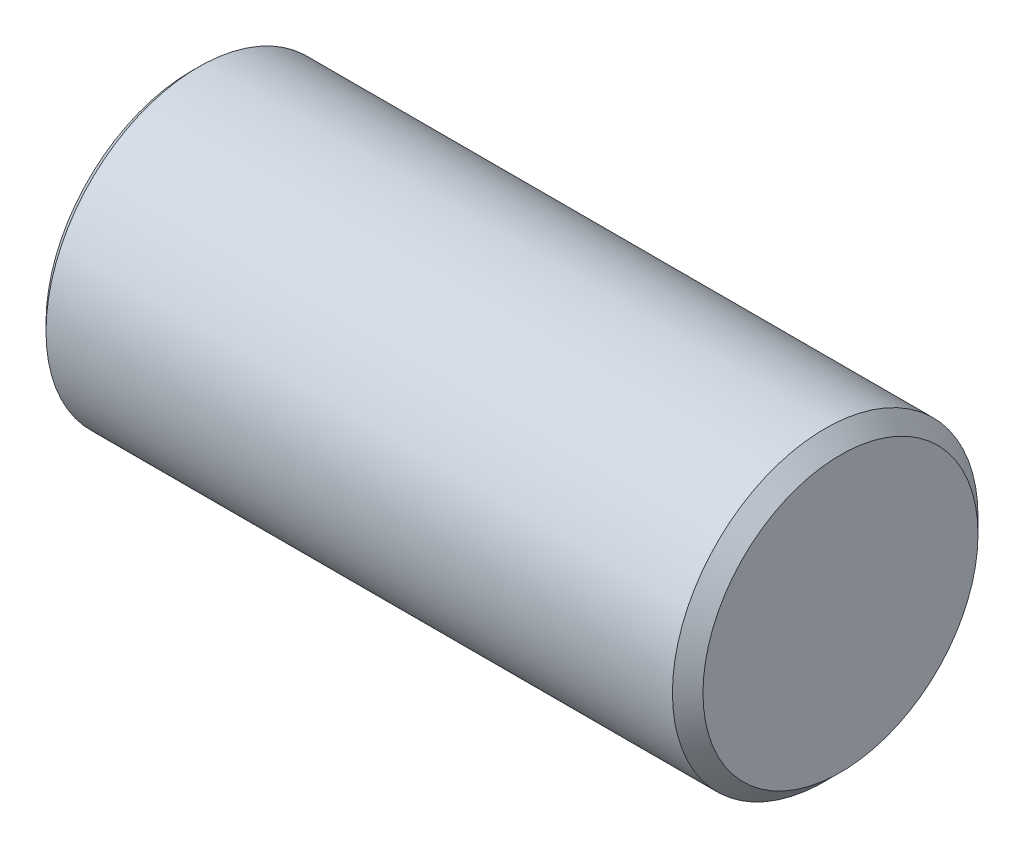
SolidWorks part; units mm, degrees
ref_plane "Спереди" through (0, 0, 0) normal (0, 0, 1) x (1, 0, 0)
ref_plane "Сверху" through (0, 0, 0) normal (0, 1, 0) x (1, 0, 0)
ref_plane "Справа" through (0, 0, 0) normal (1, 0, 0) x (0, 0, -1)
sketch "Эскиз1" plane through (0, 0, 0) normal (0, 1, 0) x (1, 0, 0)
  line L0 (92.6529, 0) -> (92.6529, 18)
  line L1 (90.6529, 20) -> (8.6529, 20)
  line L2 (7.6529, 19) -> (7.6529, 14.75)
  line L3 (7.6529, 14.75) -> (8.6529, 13.75)
  line L4 (71.6294, 0) -> (64.3183, 13.75)
  line L5 (102.994, 0) -> (-18.114, 0) construction
  line L6 (8.6529, 13.75) -> (64.3183, 13.75)
  line L7 (8.6529, 20) -> (7.6529, 19)
  line L8 (92.6529, 18) -> (90.6529, 20)
  line L9 (71.6294, 0) -> (92.6529, 0)
  point P1 (92.6529, 20)
  point P9 (7.6529, 20)
  point P10 (7.6529, 13.75)
  dimension "D1" = 1
  dimension "D2" = 45
  dimension "D3" = 1
  dimension "D4" = 45
  dimension "D5" = 2
  dimension "D6" = 45
  dimension "D7" = 6.25
  dimension "D8" = 13.75
  dimension "D9" = 20
revolve "Повернуть1" add sketch "Эскиз1" angle 360 about L5
